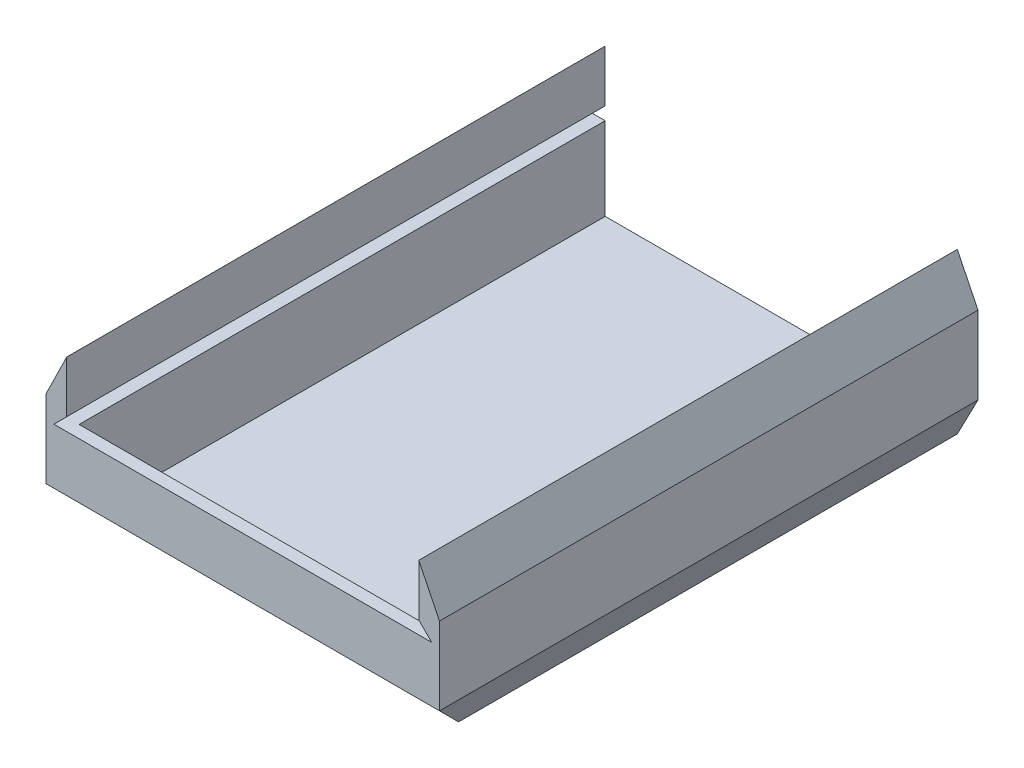
SolidWorks part; units mm, degrees
ref_plane "Front Plane" through (0, 0, 0) normal (0, 0, 1) x (1, 0, 0)
ref_plane "Top Plane" through (0, 0, 0) normal (0, 1, 0) x (1, 0, 0)
ref_plane "Right Plane" through (0, 0, 0) normal (1, 0, 0) x (0, 0, -1)
sketch "Sketch1" plane through (0, 0, 0) normal (0, 1, 0) x (1, 0, 0)
  line L1 (0, 0) -> (85, 0)
  line L2 (0, 0) -> (0, 130)
  line L3 (0, 130) -> (85, 130)
  line L4 (85, 0) -> (85, 130)
  dimension "D1" = 85
  dimension "D2" = 130
extrude "Boss-Extrude1 (Base)" add sketch "Sketch1" along normal blind 3
sketch "Sketch4" plane through (0, 0, 0) normal (0, 0, 1) x (1, 0, 0)
  line L0 (-3.1, 23) -> (0, 26.1)
  line L1 (0, 26.1) -> (0, 23)
  line L2 (0, 23) -> (-3.1, 23)
  line L3 (0, 3) -> (85, 3) construction
  line L6 (0, 3) -> (0, 0) construction
  line L7 (42.5, 28.9013) -> (42.5, -8.4397) construction
  line L8 (85, 3) -> (85, 0) construction
  line L9 (85, 23) -> (88.1, 23)
  line L10 (85, 26.1) -> (85, 23)
  line L11 (88.1, 23) -> (85, 26.1)
  dimension "D1" = 20
  dimension "D2" = 3.1
  dimension "D3" = 3.1
  dimension "D4" = 42.5
sketch "Sketch5" plane through (0, 0, 0) normal (0, 0, 1) x (1, 0, 0)
  line L11 (-5, 28.3909) -> (0, 38)
  line L12 (0, 38) -> (0, 0)
  line L13 (0, 0) -> (-5, 9.6091)
  line L14 (-5, 9.6091) -> (-5, 28.3909)
  line L16 (0, 3) -> (85, 3) construction
  line L21 (42.5, 26.5229) -> (42.5, 7.7495) construction
  line L22 (85, 3) -> (85, 0) construction
  line L23 (90, 9.6091) -> (90, 28.3909)
  line L24 (85, 0) -> (90, 9.6091)
  line L25 (85, 38) -> (85, 0)
  line L26 (90, 28.3909) -> (85, 38)
  dimension "D1" = 5
  dimension "D2" = 35
  dimension "D3" = 42.5
extrude "Boss-Extrude4 (Side Walls)" add sketch "Sketch5" against normal through all
extrude "Cut-Extrude2 (Guide Holes)" cut sketch "Sketch4" against normal through all
sketch "Sketch15" plane through (0, 0, 0) normal (0, 0, 1) x (1, 0, 0)
  line L1 (0, 23) -> (85, 23)
  line L2 (0, 23) -> (0, 3)
  line L3 (0, 3) -> (85, 3)
  line L4 (85, 23) -> (85, 3)
  line L6 (85, 23) -> (85, 3) construction
extrude "Boss-Extrude9 (Front Wall)" add sketch "Sketch15" against normal blind 3
chamfer "Chamfer5 (Front Chamfer)" distance 9.61 angle 45 1 edges at (42.5, 0, 0)
chamfer "Chamfer6 (Front Chamfer Cleanup)" distance 5 angle 45 1 edges at (42.5, 3, -3)
sketch "Sketch16" plane through (0, 0, 0) normal (0, 0, 1) x (1, 0, 0)
  line L0 (0, 26.1) -> (0, 38.6)
  line L1 (0, 38.6) -> (-5, 28.3909)
  line L2 (-5, 28.3909) -> (0, 26.1)
  line L3 (85, 0) -> (0, 0) construction
  line L5 (42.5, 0) -> (42.5, 26.995) construction
  line L6 (90, 28.3909) -> (85, 26.1)
  line L7 (85, 38.6) -> (90, 28.3909)
  line L8 (85, 26.1) -> (85, 38.6)
  dimension "D1" = 12.5
extrude "Boss-Extrude1" add sketch "Sketch16" against normal through all
